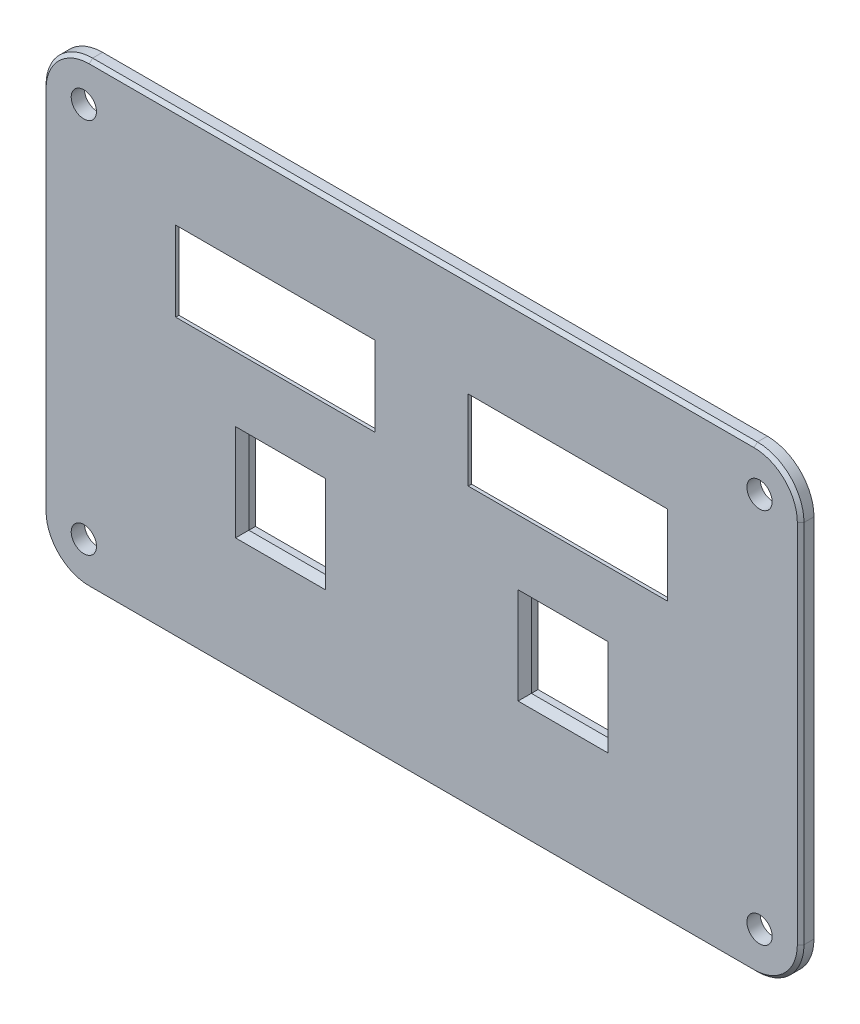
SolidWorks part; units mm, degrees
ref_plane "Front Plane" through (0, 0, 0) normal (0, 0, 1) x (1, 0, 0)
ref_plane "Top Plane" through (0, 0, 0) normal (0, 1, 0) x (1, 0, 0)
ref_plane "Right Plane" through (0, 0, 0) normal (1, 0, 0) x (0, 0, -1)
sketch "Sketch1" plane through (0, 0, 0) normal (0, 0, 1) x (1, 0, 0)
  line L0 (-57, 27.5) -> (-57, -27.5) construction
  line L1 (-50, -34.5) -> (50, -34.5) construction
  line L2 (57, -27.5) -> (57, 27.5) construction
  line L3 (50, 34.5) -> (-50, 34.5) construction
  line L4 (-57, 27.5) -> (-57, -27.5)
  line L5 (-50, -34.5) -> (50, -34.5)
  line L6 (57, -27.5) -> (57, 27.5)
  line L7 (50, 34.5) -> (-50, 34.5)
  circle A0 centre (50.814, 28.314) radius 1.5 construction
  arc A1 (-50, 34.5) -> (-57, 27.5) centre (-50, 27.5) ccw construction
  arc A2 (-57, -27.5) -> (-50, -34.5) centre (-50, -27.5) ccw construction
  arc A3 (50, -34.5) -> (57, -27.5) centre (50, -27.5) ccw construction
  arc A4 (57, 27.5) -> (50, 34.5) centre (50, 27.5) ccw construction
  circle A5 centre (-50.814, -28.314) radius 1.5 construction
  circle A6 centre (50.814, -28.314) radius 1.5 construction
  circle A7 centre (-50.814, 28.314) radius 1.5 construction
  circle A8 centre (50.814, 28.314) radius 1.5
  arc A9 (-50, 34.5) -> (-57, 27.5) centre (-50, 27.5) ccw
  arc A10 (-57, -27.5) -> (-50, -34.5) centre (-50, -27.5) ccw
  arc A11 (50, -34.5) -> (57, -27.5) centre (50, -27.5) ccw
  arc A12 (57, 27.5) -> (50, 34.5) centre (50, 27.5) ccw
  circle A13 centre (-50.814, -28.314) radius 1.5
  circle A14 centre (50.814, -28.314) radius 1.5
  circle A15 centre (-50.814, 28.314) radius 1.5
  circle A16 centre (-50.814, 28.314) radius 1.9
  circle A17 centre (50.814, 28.314) radius 1.9
  circle A18 centre (50.814, -28.314) radius 1.9
  circle A19 centre (-50.814, -28.314) radius 1.9
  dimension "D1" = 0.4
  dimension "D2" = 0.4
extrude "Boss-Extrude1" add sketch "Sketch1" along normal blind 2 contours L6 A12 L7 A9 L4 A10 L5 A11 A19 A18 A17 A16 | A15 | A13 | A14 | A8
sketch "Sketch6" plane through (0, 0, 2) normal (0, 0, 1) x (1, 0, 0)
  line L0 (-57, -9.5) -> (57, -9.5) construction
  line L1 (-27, -3.25) -> (-15.5, -3.25)
  line L2 (-27, -3.25) -> (-27, -15.75)
  line L3 (-27, -15.75) -> (-15.5, -15.75)
  line L4 (-15.5, -3.25) -> (-15.5, -15.75)
  line L5 (-27, -3.25) -> (-15.5, -15.75) construction
  line L6 (-27, -15.75) -> (-15.5, -3.25) construction
  line L7 (-57, 27.5) -> (-57, -27.5) construction
  line L8 (57, -27.5) -> (57, 27.5) construction
  line L9 (15.5, -3.25) -> (27, -3.25)
  line L10 (15.5, -3.25) -> (15.5, -15.75)
  line L11 (15.5, -15.75) -> (27, -15.75)
  line L12 (27, -3.25) -> (27, -15.75)
  line L13 (-50, -34.5) -> (50, -34.5) construction
  line L14 (0, -34.5) -> (0, 34.5) construction
  line L15 (-37, 7.5) -> (-7, 7.5)
  line L16 (-37, 7.5) -> (-37, 19.5)
  line L17 (-37, 19.5) -> (-7, 19.5)
  line L18 (-7, 7.5) -> (-7, 19.5)
  line L19 (-37, 7.5) -> (-7, 19.5) construction
  line L20 (-37, 19.5) -> (-7, 7.5) construction
  line L21 (50, 34.5) -> (-50, 34.5) construction
  line L22 (37, 19.5) -> (7, 19.5)
  line L23 (7, 7.5) -> (7, 19.5)
  line L24 (37, 7.5) -> (7, 7.5)
  line L25 (37, 7.5) -> (37, 19.5)
  point P0 (-21.25, -9.5)
  point P17 (-22, 13.5)
  dimension "D1" = 11.5
  dimension "D2" = 12.5
  dimension "D4" = 30
  dimension "D5" = 30
  dimension "D6" = 25
  dimension "D7" = 30
  dimension "D8" = 12
  dimension "D9" = 15
  dimension "D10" = 20
  dimension "D3" = 2
extrude "Cut-Extrude2" cut sketch "Sketch6" against normal blind 2
chamfer "Chamfer4" distance 1 angle 45 8 edges at (21.25, -3.25, 2) (15.5, -9.5, 2) (21.25, -15.75, 2) (27, -9.5, 2) (-21.25, -3.25, 2) (-27, -9.5, 2) (-21.25, -15.75, 2) (-15.5, -9.5, 2)
chamfer "Chamfer5" distance 1.5 angle 60 8 edges at (7, 13.5, 0) (22, 19.5, 0) (37, 13.5, 0) (22, 7.5, 0) (-37, 13.5, 0) (-22, 19.5, 0) (-7, 13.5, 0) (-22, 7.5, 0)
chamfer "Chamfer6" distance 0.5 angle 45 8 edges at (57, 0, 2) (54.9497, 32.4497, 2) (54.9497, -32.4497, 2) (0, 34.5, 2) (0, -34.5, 2) (-54.9497, 32.4497, 2) (-54.9497, -32.4497, 2) (-57, 0, 2)
